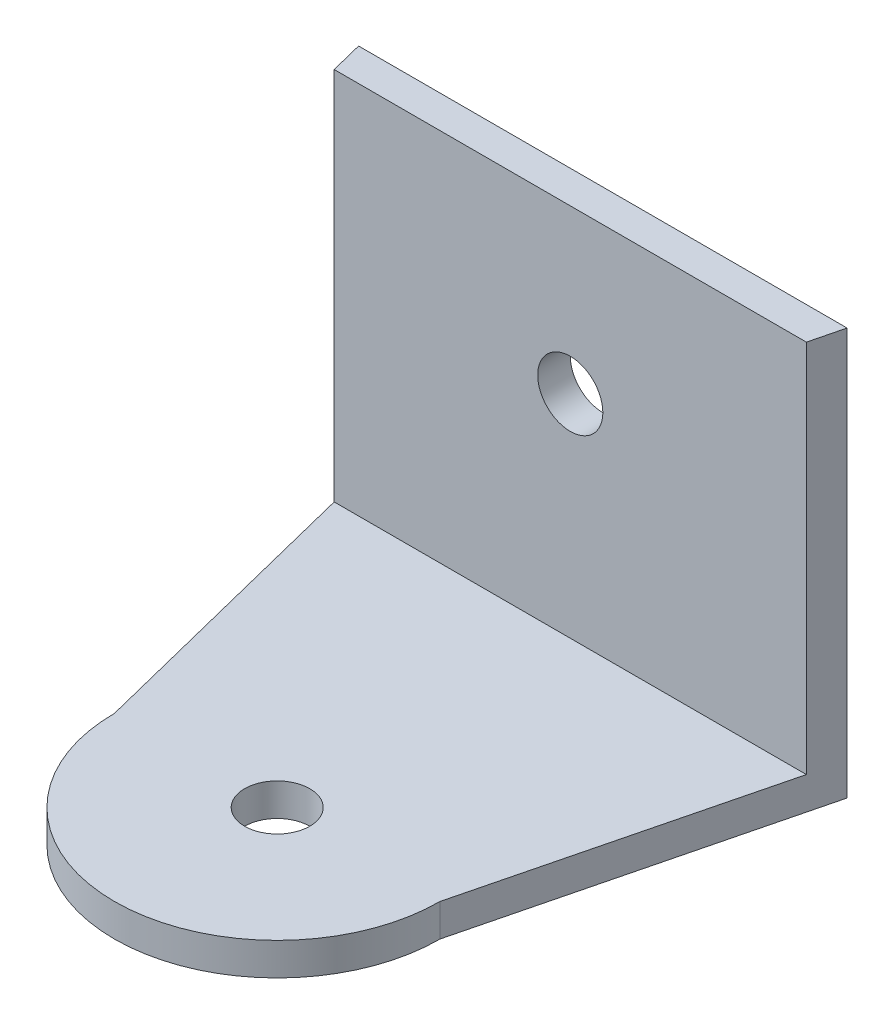
SolidWorks part; units mm, degrees
ref_plane "Front Plane" through (0, 0, 0) normal (0, 0, 1) x (1, 0, 0)
ref_plane "Top Plane" through (0, 0, 0) normal (0, 1, 0) x (1, 0, 0)
ref_plane "Right Plane" through (0, 0, 0) normal (1, 0, 0) x (0, 0, -1)
sketch "Sketch1" plane through (0, 0, 0) normal (0, 0, 1) x (1, 0, 0)
  line L1 (-15, 12.5) -> (15, 12.5)
  line L2 (-15, 12.5) -> (-15, -12.5)
  line L3 (-15, -12.5) -> (15, -12.5)
  line L4 (15, 12.5) -> (15, -12.5)
  line L5 (-15, 12.5) -> (15, -12.5) construction
  line L6 (-15, -12.5) -> (15, 12.5) construction
  point P0 (0, 0)
  dimension "D1" = 30
  dimension "D2" = 25
extrude "Boss-Extrude1" add sketch "Sketch1" along normal blind 2
sketch "Sketch2" plane through (0, 0, 2) normal (0, 0, 1) x (1, 0, 0)
  line L1 (15, -12.5) -> (15, 12.5) construction
  line L2 (-15, -12.5) -> (15, -12.5) construction
  circle A0 centre (0, 2.5) radius 2
  dimension "D1" = 4
  dimension "D2" = 15
  dimension "D3" = 15
extrude "Cut-Extrude1" cut sketch "Sketch2" against normal blind 2
sketch "Sketch3" plane through (0, 0, 2) normal (0, 0, 1) x (1, 0, 0)
  line L0 (15, -12.5) -> (15, 12.5) construction
  line L1 (-15, -12.5) -> (15, -12.5)
  line L2 (-15, -12.5) -> (-15, -10.5)
  line L3 (-15, -10.5) -> (15, -10.5)
  line L4 (15, -12.5) -> (15, -10.5)
  dimension "D1" = 2
extrude "Boss-Extrude3" add sketch "Sketch3" along normal blind 28
sketch "Sketch4" plane through (0, -12.5, 0) normal (0, -1, 0) x (1, 0, 0)
  line L0 (15, 30) -> (15, 0) construction
  line L1 (-15, 30) -> (15, 30) construction
  line L2 (-15, 0) -> (-10, 20)
  line L3 (15, 0) -> (10, 20)
  circle A0 centre (0, 20) radius 2
  arc A1 (10, 20) -> (-10, 20) centre (0, 20) ccw
  line M3 (15, 0) -> (15, 30)
  line M4 (15, 30) -> (-15, 30)
  line M5 (-15, 30) -> (-15, 0)
  dimension "D1" = 4
  dimension "D2" = 15
  dimension "D3" = 10
extrude "Cut-Extrude2" cut sketch "Sketch4" against normal through all contours A0 | A1 L2 M4 M5 | A1 L3 M3 M4
